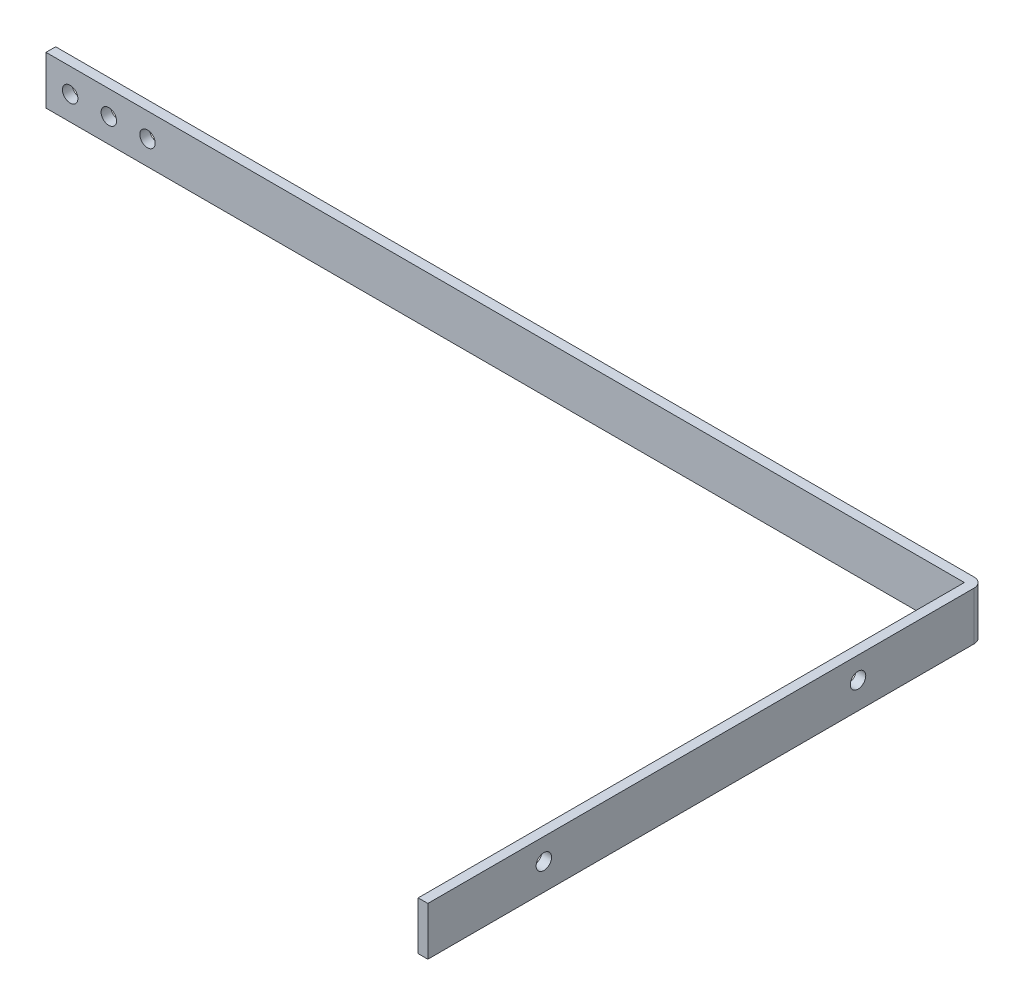
SolidWorks part; units mm, degrees
ref_plane "Plan de face" through (0, 0, 0) normal (0, 0, 1) x (1, 0, 0)
ref_plane "Plan de dessus" through (0, 0, 0) normal (0, 1, 0) x (1, 0, 0)
ref_plane "Plan de droite" through (0, 0, 0) normal (1, 0, 0) x (0, 0, -1)
sketch "Esquisse1" plane through (0, 0, 0) normal (0, 0, 1) x (1, 0, 0)
  line L0 (0, 0) -> (0, 10)
  line L1 (0, 10) -> (190, 10)
  line L2 (190, 10) -> (190, 0)
  line L3 (190, 0) -> (0, 0)
  circle A0 centre (5, 5) radius 1.6
  circle A1 centre (13, 5) radius 1.6
  circle A2 centre (21, 5) radius 1.6
  dimension "D3" = 3.2
  dimension "D6" = 3
  dimension "D1" = 190
  dimension "D2" = 10
  dimension "D4" = 5
  dimension "D5" = 5
  dimension "D7" = 16
extrude "Boss.-Extru.1" add sketch "Esquisse1" along normal blind 2
sketch "Esquisse2" plane through (0, 0, 0) normal (0, 0, 1) x (1, 0, 0)
  line L0 (190, 10) -> (192, 10)
  line L1 (192, 10) -> (192, 0)
  line L2 (192, 0) -> (190, 0)
  line L3 (190, 0) -> (190, 10)
  dimension "D1" = 2
extrude "Boss.-Extru.2" add sketch "Esquisse2" along normal blind 115
fillet "Congé1" radius 2 1 edges at (192, 5, 0)
sketch "Esquisse3" plane through (192, 0, 0) normal (1, 0, 0) x (0, 0, -1)
  circle A0 centre (-91, 5.5) radius 1.6
  circle A1 centre (-26, 5.5) radius 1.6
  dimension "D1" = 3.2
  dimension "D2" = 4.5
  dimension "D3" = 24
  dimension "D4" = 65
extrude "Enlèv. mat.-Extru.1" cut sketch "Esquisse3" against normal up to next
